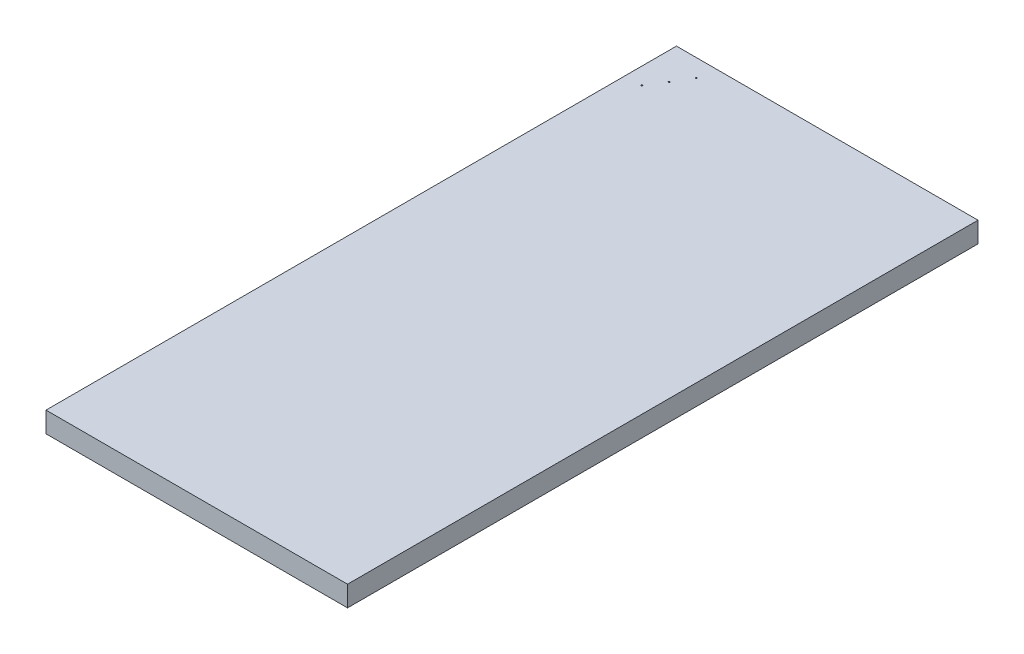
SolidWorks part; units mm, degrees
ref_plane "Front Plane" through (0, 0, 0) normal (0, 0, 1) x (1, 0, 0)
ref_plane "Top Plane" through (0, 0, 0) normal (0, 1, 0) x (1, 0, 0)
ref_plane "Right Plane" through (0, 0, 0) normal (1, 0, 0) x (0, 0, -1)
sketch "Sketch1" plane through (0, 0, 0) normal (0, 1, 0) x (1, 0, 0)
  line L1 (-139.2879, 131.2521) -> (140.1121, 131.2521)
  line L2 (-139.2879, 131.2521) -> (-139.2879, -452.9479)
  line L3 (-139.2879, -452.9479) -> (140.1121, -452.9479)
  line L4 (140.1121, 131.2521) -> (140.1121, -452.9479)
  dimension "D1" = 279.4
  dimension "D2" = 584.2
extrude "Boss-Extrude1" add sketch "Sketch1" along normal blind 19.05
sketch "Sketch2" plane through (0, 19.05, 0) normal (0, 1, 0) x (1, 0, 0)
  line L0 (-139.2879, 77.4997) -> (-105.4806, 131.2521) construction
  line L1 (-139.2879, 131.2521) -> (-139.2879, -452.9479) construction
  line L2 (140.1121, 131.2521) -> (-139.2879, 131.2521) construction
  line L3 (-105.4806, 131.2521) -> (-89.3549, 121.1099) construction
  line L4 (-89.3549, 121.1099) -> (-123.1622, 67.3575) construction
  line L5 (-123.1622, 67.3575) -> (-139.2879, 77.4997) construction
  line L6 (-123.8877, 83.7195) -> (-113.9226, 99.054) construction
  line L7 (-122.3842, 104.3759) -> (-106.2585, 94.2337) construction
  line L8 (-104.4169, 114.6774) -> (-113.9226, 99.054) construction
  circle A0 centre (-113.9226, 99.054) radius 0.635
  circle A1 centre (-104.4169, 114.6774) radius 0.635
  circle A2 centre (-123.8877, 83.7195) radius 0.635
  point P10 (-131.2251, 72.4286)
  dimension "D4" = 1.27
  dimension "D1" = 19.05
  dimension "D2" = 63.5
  dimension "D3" = 18.288
extrude "Cut-Extrude1" cut sketch "Sketch2" against normal through all both and the other way through all
